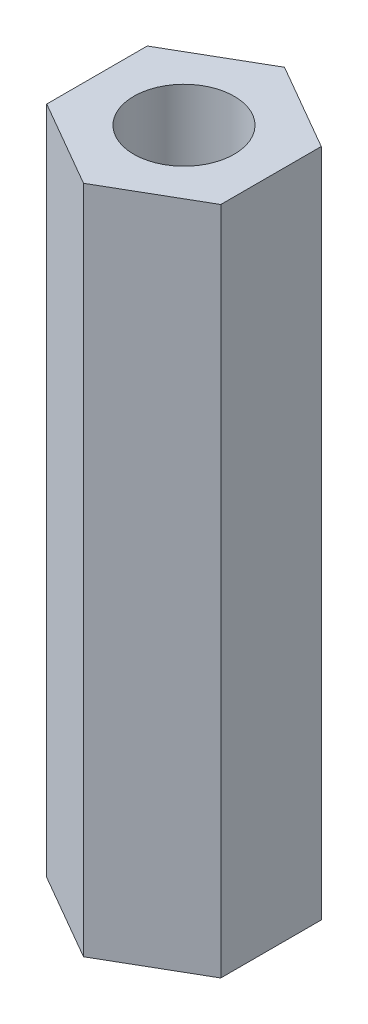
SolidWorks part; units mm, degrees
ref_plane "Спереди" through (0, 0, 0) normal (0, 0, 1) x (1, 0, 0)
ref_plane "Сверху" through (0, 0, 0) normal (0, 1, 0) x (1, 0, 0)
ref_plane "Справа" through (0, 0, 0) normal (1, 0, 0) x (0, 0, -1)
other "Configuration Table"
sketch "Эскиз1" plane through (0, 0, 0) normal (0, 1, 0) x (1, 0, 0)
  line L3 (2.5981, 1.5) -> (0, 3)
  line L4 (-2.5981, 1.5) -> (0, 3)
  line L5 (-2.5981, 1.5) -> (-2.5981, -1.5)
  line L6 (2.5981, 1.5) -> (2.5981, -1.5)
  line L7 (-2.5981, -1.5) -> (0, -3)
  line L8 (0, -3) -> (2.5981, -1.5)
  circle A1 centre (0, 0) radius 3
  circle A6 centre (0, 0) radius 1.5
extrude "Бобышка-Вытянуть1" add sketch "Эскиз1" along normal blind 20 contours L7 L8 L6 L3 L4 L5 A6
